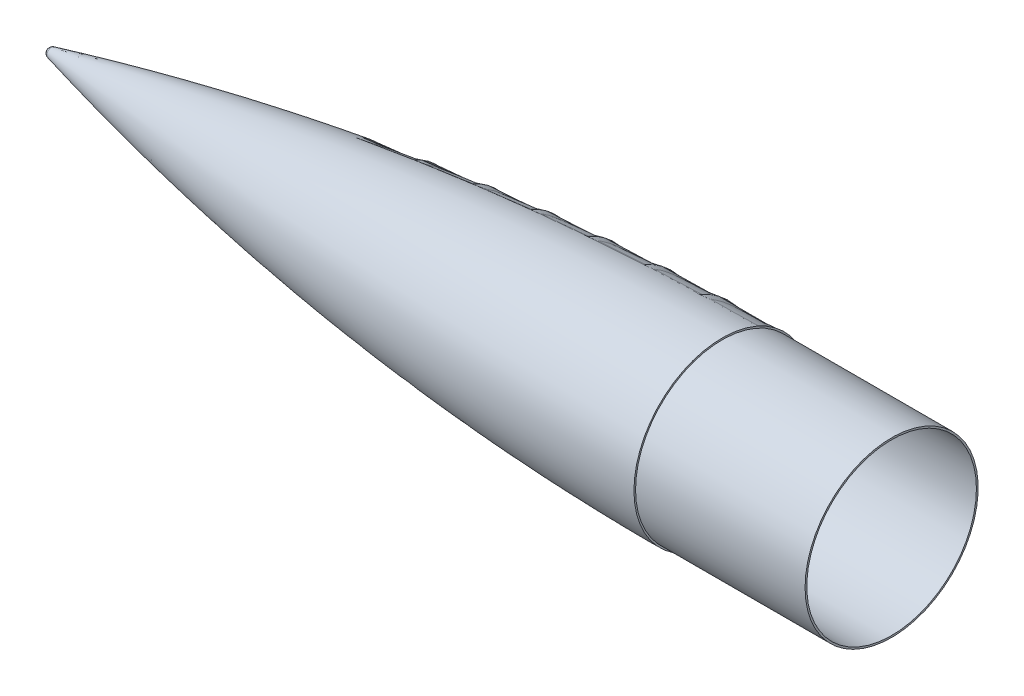
SolidWorks part; units mm, degrees
ref_plane "Front Plane" through (0, 0, 0) normal (0, 0, 1) x (1, 0, 0)
ref_plane "Top Plane" through (0, 0, 0) normal (0, 1, 0) x (1, 0, 0)
ref_plane "Right Plane" through (0, 0, 0) normal (1, 0, 0) x (0, 0, -1)
sketch "Sketch2" plane through (0, 0, 0) normal (0, 0, 1) x (1, 0, 0)
  line L0 (0, 0) -> (183.1669, 0) construction
  line L1 (606.232, 76.2) -> (755.457, 76.2)
  line L2 (85.3846, 0) -> (-85.3846, 0) construction
  line L3 (606.232, 77.6224) -> (606.232, 76.2)
  line L4 (755.457, 76.2) -> (755.457, 0)
  line L5 (0, 0) -> (755.457, 0)
  arc A0 (15.8245, 3.9995) -> (12.7, 0) centre (16.822, 0) ccw
  spline S0 degree 2 poles (-59.258, -15.9165) (303.7986, 86.1434) (666.8552, 76.8462) knots 0 0 0 1 1 1 construction
  spline S1 degree 2 poles (0, 0) (303.116, 77.6224) (606.232, 77.6224) knots 0.08161 0.08161 0.08161 0.91651 0.91651 0.91651
  point P15 (0, 0)
  dimension "D1" = 149.225
  dimension "D3" = 76.2
  dimension "D2" = 77.6224
  dimension "D4" = 12.7
revolve "Revolve2" add sketch "Sketch2" angle 360 about L0
shell "Shell2" thickness 1.524
equation "\"nose_thickness\"= 0.056"
equation "\"base_diameter\"= 6.112"
equation "\"L\" = 23.8674"
equation "\"D3@Sketch2\"=\"base_diameter\"/2 - \"nose_thickness\""
equation "\"D2@Sketch2\"=\"base_diameter\"/2"
equation "\"D4@Sketch2\"=.5"
equation "\"Kprime\"= 1"
